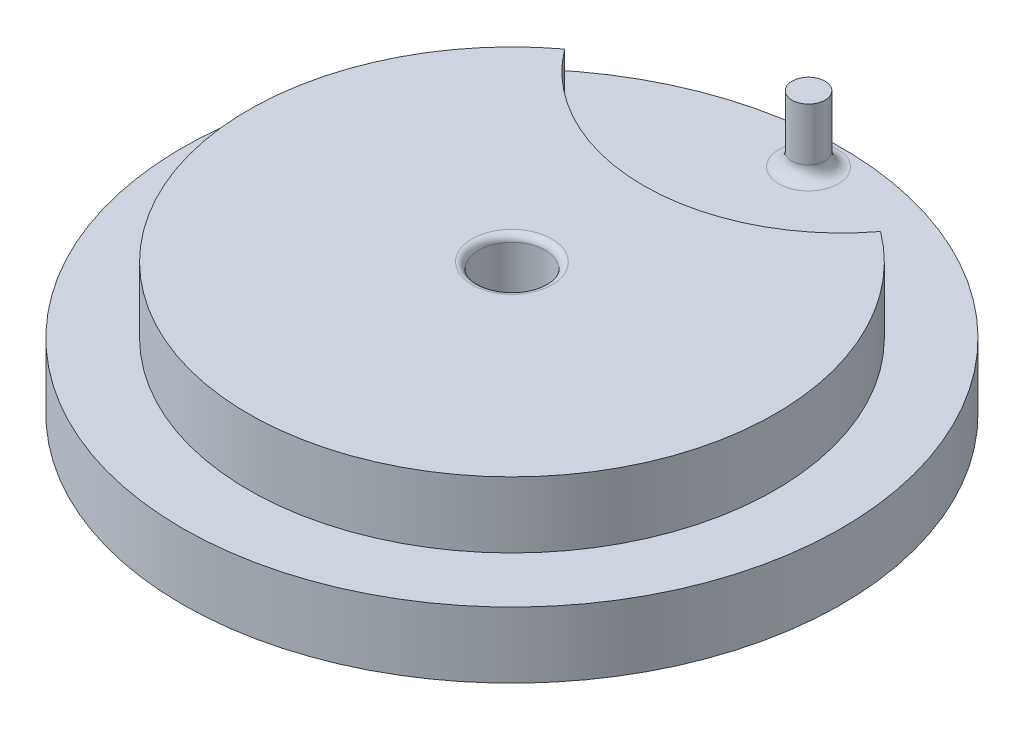
SolidWorks part; units mm, degrees
ref_plane "Front Plane" through (0, 0, 0) normal (0, 0, 1) x (1, 0, 0)
ref_plane "Top Plane" through (0, 0, 0) normal (0, 1, 0) x (1, 0, 0)
ref_plane "Right Plane" through (0, 0, 0) normal (1, 0, 0) x (0, 0, -1)
sketch "Sketch1" plane through (0, 0, 0) normal (0, 1, 0) x (1, 0, 0)
  circle A0 centre (0, 0) radius 63.5
  circle A1 centre (0, 0) radius 6.4135
  dimension "D1" = 127
  dimension "D2" = 12.827
extrude "Boss-Extrude1" add sketch "Sketch1" along normal blind 12.7
sketch "Sketch2" plane through (0, 12.7, 0) normal (0, 1, 0) x (1, 0, 0)
  circle A0 centre (0, 0) radius 50.7365
  circle A1 centre (0, 0) radius 6.4135
  dimension "D1" = 101.473
  dimension "D2" = 12.827
extrude "Boss-Extrude2" add sketch "Sketch2" along normal blind 12.7
sketch "Sketch3" plane through (0, 25.4, 0) normal (0, 1, 0) x (1, 0, 0)
  line L0 (0, 0) -> (0, 106.9417) construction
  circle A0 centre (0, 63.5) radius 38.1
  dimension "D2" = 76.2
  dimension "D1" = 63.5
extrude "Cut-Extrude2" cut sketch "Sketch3" against normal up to surface (12.7 mm away) contours A0 up to face at (0, 12.7, 50.7365)
sketch "Sketch4" plane through (0, 12.7, 0) normal (0, 1, 0) x (1, 0, 0)
  line L0 (0, 0) -> (0, 102.0016) construction
  circle A0 centre (0, 57.15) radius 3.175
  dimension "D1" = 6.35
  dimension "D2" = 57.15
extrude "Boss-Extrude3" add sketch "Sketch4" along normal blind 12.7
fillet "Fillet1" radius 2.54 1 edges at (0, 12.7, -53.975)
fillet "Fillet2" radius 5.08 1 edges at (0, 0, 6.4135)
fillet "Fillet3" radius 1.27 1 edges at (0, 25.4, 6.4135)
